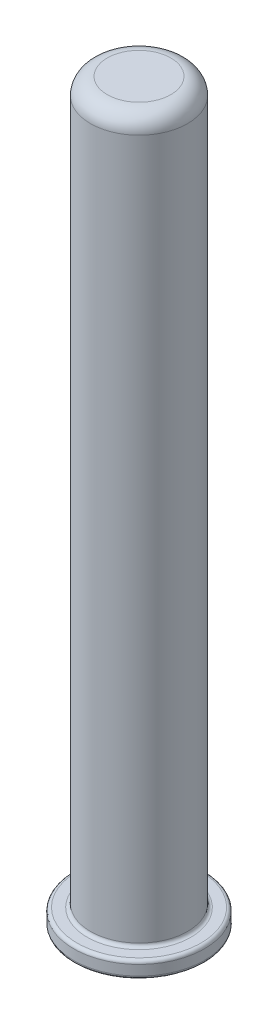
SolidWorks part; units mm, degrees
ref_plane "Front Plane" through (0, 0, 0) normal (0, 0, 1) x (1, 0, 0)
ref_plane "Top Plane" through (0, 0, 0) normal (0, 1, 0) x (1, 0, 0)
ref_plane "Right Plane" through (0, 0, 0) normal (1, 0, 0) x (0, 0, -1)
sketch "Sketch2" plane through (0, 0, 0) normal (0, 1, 0) x (1, 0, 0)
  circle A0 centre (0, 0) radius 14.5
  dimension "D1" = 29
extrude "Boss-Extrude1" add sketch "Sketch2" along normal blind 220
fillet "Fillet1" radius 5 1 edges at (0, 220, 14.5)
sketch "Sketch3" plane through (0, 0, 0) normal (0, -1, 0) x (1, 0, 0)
  circle A0 centre (0, 0) radius 19.5
  circle A1 centre (0, 0) radius 14.5 construction
  dimension "D1" = 5
extrude "Boss-Extrude2" add sketch "Sketch3" against normal blind 5
fillet "Fillet2" radius 1 3 edges at (0, 5, -19.5) (0, 0, -19.5) (0, 5, -14.5)
